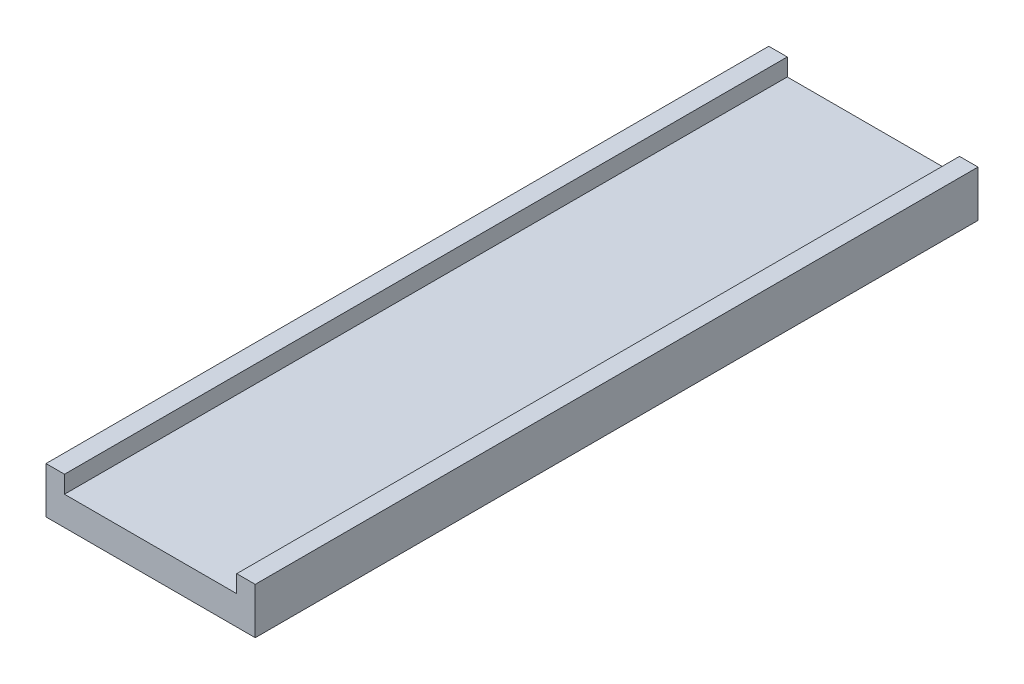
SolidWorks part; units mm, degrees
ref_plane "Спереди" through (0, 0, 0) normal (0, 0, 1) x (1, 0, 0)
ref_plane "Сверху" through (0, 0, 0) normal (0, 1, 0) x (1, 0, 0)
ref_plane "Справа" through (0, 0, 0) normal (1, 0, 0) x (0, 0, -1)
sketch "Эскиз1" plane through (0, 0, 0) normal (0, 0, 1) x (1, 0, 0)
  line L0 (-36.1861, 0) -> (36.1861, 0)
  line L1 (36.1861, 0) -> (36.1861, 16)
  line L2 (36.1861, 16) -> (29.7888, 16)
  line L3 (29.7888, 16) -> (29.7888, 10)
  line L4 (29.7888, 10) -> (-29.7888, 10)
  line L5 (-29.7888, 10) -> (-29.7888, 16)
  line L6 (-29.7888, 16) -> (-36.1861, 16)
  line L7 (-36.1861, 16) -> (-36.1861, 0)
  point P4 (0, 0)
  dimension "D1" = 16
  dimension "D2" = 6
extrude "Бобышка-Вытянуть1" add sketch "Эскиз1" along normal blind 250
